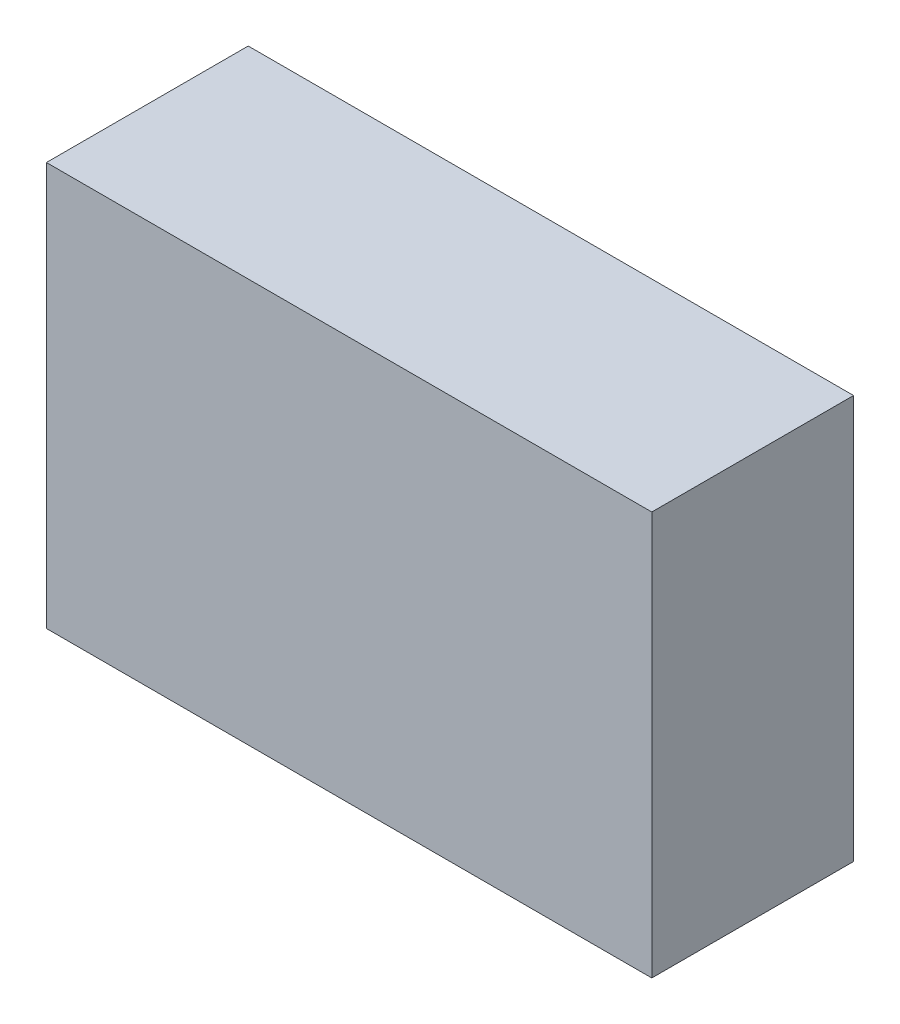
SolidWorks part; units mm, degrees
ref_plane "Front Plane" through (0, 0, 0) normal (0, 0, 1) x (1, 0, 0)
ref_plane "Top Plane" through (0, 0, 0) normal (0, 1, 0) x (1, 0, 0)
ref_plane "Right Plane" through (0, 0, 0) normal (1, 0, 0) x (0, 0, -1)
sketch "Sketch2" plane through (0, 0, 0) normal (0, 0, 1) x (1, 0, 0)
  line L1 (0, 0) -> (3, 0)
  line L2 (0, 0) -> (0, 2)
  line L3 (0, 2) -> (3, 2)
  line L4 (3, 0) -> (3, 2)
  dimension "D1" = 2
  dimension "D2" = 3
extrude "Boss-Extrude1" add sketch "Sketch2" along normal blind 1
